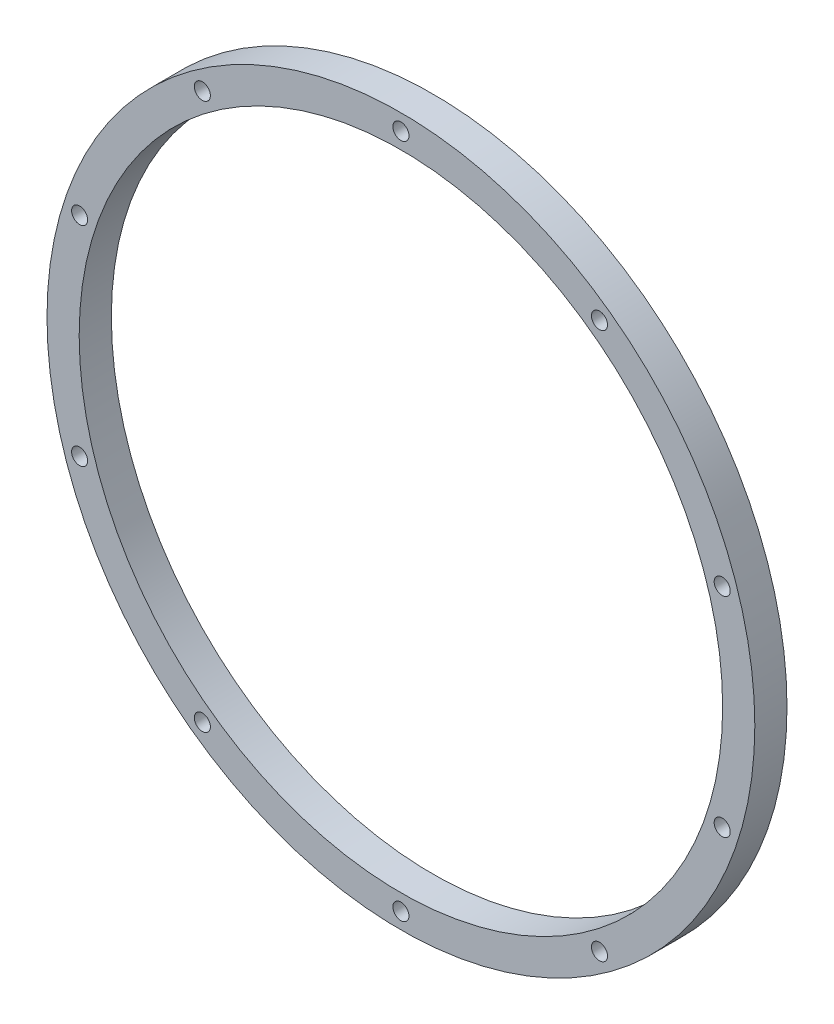
SolidWorks part; units mm, degrees
material "Простая углеродистая сталь"
ref_plane "Спереди" through (0, 0, 0) normal (0, 0, 1) x (1, 0, 0)
ref_plane "Сверху" through (0, 0, 0) normal (0, 1, 0) x (1, 0, 0)
ref_plane "Справа" through (0, 0, 0) normal (1, 0, 0) x (0, 0, -1)
sketch "Эскиз1" plane through (0, 0, 0) normal (0, 0, 1) x (1, 0, 0)
  circle A0 centre (0, 0) radius 117
  circle A1 centre (0, 0) radius 128.7
extrude "Бобышка-Вытянуть2" add sketch "Эскиз1" against normal blind 11.7
sketch "Эскиз2" plane through (0, 0, 0) normal (0, 0, 1) x (1, 0, 0)
  circle A1 centre (0, 122.85) radius 2.925
extrude "Вырез-Вытянуть2" cut sketch "Эскиз2" against normal through all
pattern_circular "Круговой массив1" count 10 over 360 about axis through (0, 0, 0) along (0, 0, 1) of "Вырез-Вытянуть2"
